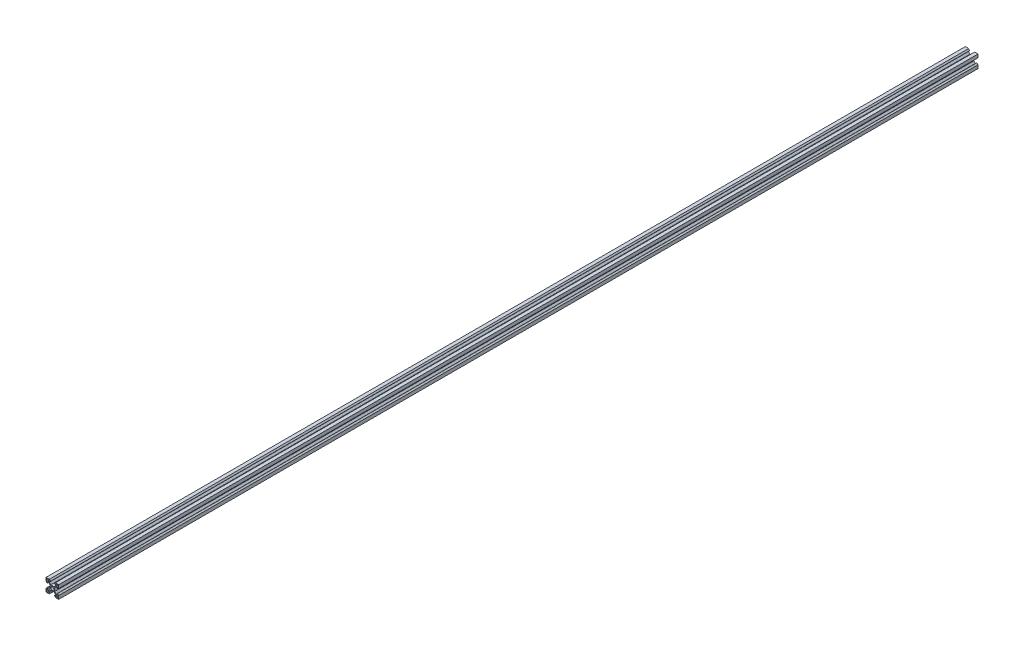
SolidWorks part; units mm, degrees
ref_plane "Спереди" through (0, 0, 0) normal (0, 0, 1) x (1, 0, 0)
ref_plane "Сверху" through (0, 0, 0) normal (0, 1, 0) x (1, 0, 0)
ref_plane "Справа" through (0, 0, 0) normal (1, 0, 0) x (0, 0, -1)
sketch "Эскиз1" plane through (0, 0, 0) normal (0, 0, 1) x (1, 0, 0)
  line L0 (-7.5, 7.5) -> (7.5, 7.5) construction
  line L1 (-10, -10) -> (10, -10) construction
  line L2 (-10, -10) -> (-10, 10) construction
  line L3 (-10, 10) -> (-4.75, 10)
  line L4 (10, -10) -> (10, 10) construction
  line L5 (-10, -10) -> (10, 10) construction
  line L6 (-10, 10) -> (10, -10) construction
  line L7 (7.5, 7.5) -> (7.5, -7.5) construction
  line L8 (7.5, -7.5) -> (-7.5, -7.5) construction
  line L9 (-7.5, -7.5) -> (-7.5, 7.5) construction
  line L10 (-7.5, 7.5) -> (7.5, -7.5) construction
  line L11 (-7.5, -7.5) -> (7.5, 7.5) construction
  line L12 (-4.75, 10) -> (-3.1, 8)
  line L13 (-3.1, 8) -> (-4.95, 8)
  line L14 (-4.95, 8) -> (-4.95, 5.85)
  line L15 (-4.95, 5.85) -> (-2.6, 3.5)
  line L16 (-2.6, 3.5) -> (2.6, 3.5)
  line L17 (2.6, 3.5) -> (4.95, 5.85)
  line L18 (4.95, 5.85) -> (4.95, 8)
  line L19 (4.95, 8) -> (3.1, 8)
  line L20 (3.1, 8) -> (4.75, 10)
  line L21 (4.75, 10) -> (10, 10)
  line L22 (-4.75, 10) -> (4.75, 10) construction
  line L23 (-3.1, 8) -> (3.1, 8) construction
  line L24 (-4.95, 5.85) -> (4.95, 5.85) construction
  line L25 (-2.6, 3.5) -> (0, 0) construction
  line L26 (-9.15, 5.85) -> (-5.85, 5.85)
  line L27 (-9.15, 5.85) -> (-9.15, 9.15)
  line L28 (-9.15, 9.15) -> (-5.85, 9.15)
  line L29 (-5.85, 5.85) -> (-5.85, 9.15)
  line L30 (-9.15, 5.85) -> (-5.85, 9.15) construction
  line L31 (-9.15, 9.15) -> (-5.85, 5.85) construction
  line L32 (9.15, 5.85) -> (5.85, 5.85)
  line L33 (9.15, 5.85) -> (9.15, 9.15)
  line L34 (9.15, 9.15) -> (5.85, 9.15)
  line L35 (5.85, 5.85) -> (5.85, 9.15)
  line L36 (9.15, 5.85) -> (5.85, 9.15) construction
  line L37 (9.15, 9.15) -> (5.85, 5.85) construction
  line L38 (9.15, -9.15) -> (5.85, -9.15)
  line L39 (9.15, -9.15) -> (9.15, -5.85)
  line L40 (9.15, -5.85) -> (5.85, -5.85)
  line L41 (5.85, -9.15) -> (5.85, -5.85)
  line L42 (9.15, -9.15) -> (5.85, -5.85) construction
  line L43 (9.15, -5.85) -> (5.85, -9.15) construction
  line L44 (-9.15, -5.85) -> (-5.85, -5.85)
  line L45 (-9.15, -5.85) -> (-9.15, -9.15)
  line L46 (-9.15, -9.15) -> (-5.85, -9.15)
  line L47 (-5.85, -5.85) -> (-5.85, -9.15)
  line L48 (-9.15, -5.85) -> (-5.85, -9.15) construction
  line L49 (-9.15, -9.15) -> (-5.85, -5.85) construction
  line L50 (3.5, 2.6) -> (0, 0) construction
  line L51 (3.5, 2.6) -> (3.5, -2.6)
  line L52 (5.85, 4.95) -> (3.5, 2.6)
  line L53 (3.5, -2.6) -> (5.85, -4.95)
  line L54 (5.85, -4.95) -> (8, -4.95)
  line L55 (8, -4.95) -> (8, -3.1)
  line L56 (8, -3.1) -> (10, -4.75)
  line L57 (8, 4.95) -> (5.85, 4.95)
  line L58 (8, 3.1) -> (8, 4.95)
  line L59 (10, 4.75) -> (8, 3.1)
  line L60 (2.6, -3.5) -> (0, 0) construction
  line L61 (2.6, -3.5) -> (-2.6, -3.5)
  line L62 (4.95, -5.85) -> (2.6, -3.5)
  line L63 (-2.6, -3.5) -> (-4.95, -5.85)
  line L64 (-4.95, -5.85) -> (-4.95, -8)
  line L65 (-4.95, -8) -> (-3.1, -8)
  line L66 (-3.1, -8) -> (-4.75, -10)
  line L67 (4.95, -8) -> (4.95, -5.85)
  line L68 (3.1, -8) -> (4.95, -8)
  line L69 (4.75, -10) -> (3.1, -8)
  line L70 (-3.5, -2.6) -> (0, 0) construction
  line L71 (-3.5, -2.6) -> (-3.5, 2.6)
  line L72 (-5.85, -4.95) -> (-3.5, -2.6)
  line L73 (-3.5, 2.6) -> (-5.85, 4.95)
  line L74 (-5.85, 4.95) -> (-8, 4.95)
  line L75 (-8, 4.95) -> (-8, 3.1)
  line L76 (-8, 3.1) -> (-10, 4.75)
  line L77 (-8, -4.95) -> (-5.85, -4.95)
  line L78 (-8, -3.1) -> (-8, -4.95)
  line L79 (-10, -4.75) -> (-8, -3.1)
  line L80 (-10, 10) -> (-10, 4.75)
  line L81 (-10, -4.75) -> (-10, -10)
  line L82 (-10, -10) -> (-4.75, -10)
  line L83 (4.75, -10) -> (10, -10)
  line L84 (10, -10) -> (10, -4.75)
  line L85 (10, 4.75) -> (10, 10)
  circle A0 centre (-7.5, 7.5) radius 1.65 construction
  circle A1 centre (7.5, 7.5) radius 1.65 construction
  circle A2 centre (7.5, -7.5) radius 1.65 construction
  circle A3 centre (-7.5, -7.5) radius 1.65 construction
  circle A4 centre (0, 0) radius 2.5
  point P0 (0, 0)
  point P14 (0, 0)
  point P15 (0, 3.5)
  point P26 (0, 5.85)
  point P27 (0, 8)
  point P28 (0, 10)
  point P80 (0, 0)
  dimension "D3" = 3.3
  dimension "D4" = 3.3
  dimension "D5" = 3.3
  dimension "D6" = 3.3
  dimension "D14" = 5
  dimension "D1" = 20
  dimension "D2" = 20
  dimension "D7" = 15
  dimension "D8" = 6.2
  dimension "D9" = 9.9
  dimension "D10" = 9.5
  dimension "D11" = 2
  dimension "D12" = 6.5
  dimension "D15" = 4
extrude "Бобышка-Вытянуть1" add sketch "Эскиз1" against normal up to surface (1445 mm away)
